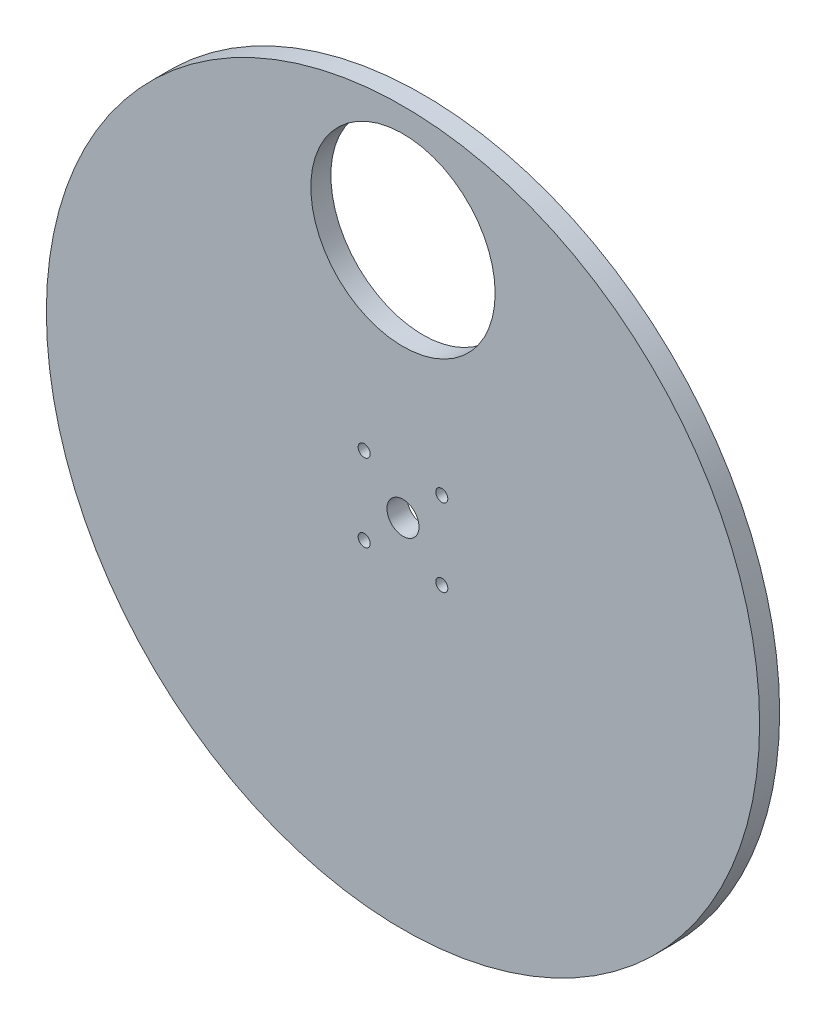
SolidWorks part; units mm, degrees
ref_plane "Front Plane" through (0, 0, 0) normal (0, 0, 1) x (1, 0, 0)
ref_plane "Top Plane" through (0, 0, 0) normal (0, 1, 0) x (1, 0, 0)
ref_plane "Right Plane" through (0, 0, 0) normal (1, 0, 0) x (0, 0, -1)
sketch "Sketch1" plane through (0, 0, 0) normal (0, 0, 1) x (1, 0, 0)
  line L0 (0, 0) -> (0, 89) construction
  circle A0 centre (0, 0) radius 89
  circle A1 centre (0, 0) radius 4
  circle A2 centre (-9.6862, 9.6862) radius 1.5
  circle A3 centre (0, 60) radius 23
  circle A4 centre (9.6862, 9.6862) radius 1.5
  circle A5 centre (9.6862, -9.6862) radius 1.5
  circle A6 centre (-9.6862, -9.6862) radius 1.5
  dimension "D1" = 178
  dimension "D2" = 8
extrude "Boss-Extrude1" add sketch "Sketch1" along normal blind 5
